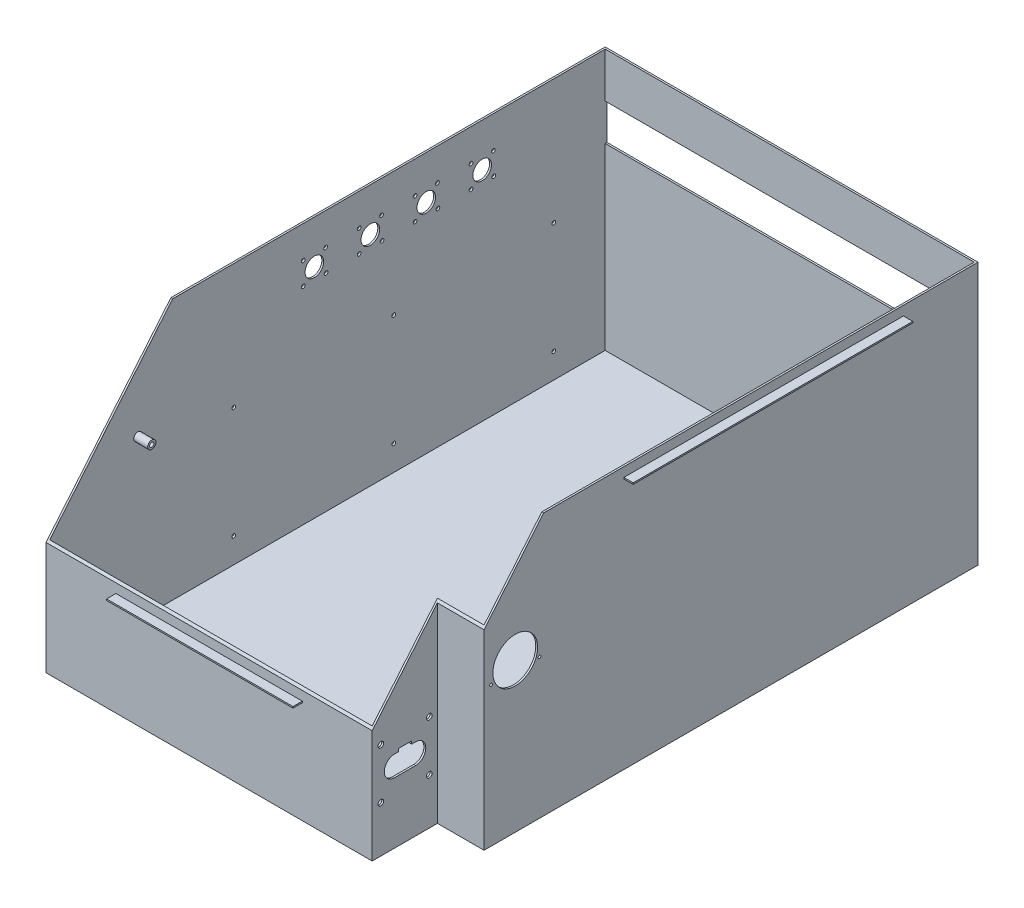
SolidWorks part; units mm, degrees
ref_plane "Front Plane" through (0, 0, 0) normal (0, 0, 1) x (1, 0, 0)
ref_plane "Top Plane" through (0, 0, 0) normal (0, 1, 0) x (1, 0, 0)
ref_plane "Right Plane" through (0, 0, 0) normal (1, 0, 0) x (0, 0, -1)
sketch "Sketch1" plane through (0, 0, 0) normal (0, 1, 0) x (1, 0, 0)
  line L1 (-200, 237.8263) -> (200, 237.8263)
  line L2 (-200, 237.8263) -> (-200, -362.1737)
  line L3 (-200, -362.1737) -> (150, -362.1737)
  line L4 (200, 237.8263) -> (200, -292.1737)
  line L6 (200, -292.1737) -> (150, -292.1737)
  line L7 (150, -292.1737) -> (150, -362.1737)
  line L8 (0, -55) -> (0, 55) construction
  point P1 (0, 237.8263)
  dimension "D1" = 600
  dimension "D2" = 400
  dimension "D5" = 70
  dimension "D6" = 50
extrude "Boss-Extrude1" add sketch "Sketch1" along normal blind 1.5
sketch "Sketch2" plane through (0, 1.5, 0) normal (0, 1, 0) x (1, 0, 0)
  line L60 (-198, 235.8263) -> (-198, -360.1737)
  line L61 (-198, -360.1737) -> (148, -360.1737)
  line L62 (148, -360.1737) -> (148, -290.1737)
  line L63 (148, -290.1737) -> (198, -290.1737)
  line L64 (198, -290.1737) -> (198, 235.8263)
  line L65 (198, 235.8263) -> (-198, 235.8263)
  line L66 (-200, 237.8263) -> (-200, -362.1737)
  line L67 (-200, -362.1737) -> (150, -362.1737)
  line L68 (150, -362.1737) -> (150, -292.1737)
  line L69 (150, -292.1737) -> (200, -292.1737)
  line L70 (200, -292.1737) -> (200, 237.8263)
  line L71 (200, 237.8263) -> (-200, 237.8263)
  line L72 (-200, 237.8263) -> (-200, -362.1737)
  line L73 (-200, -362.1737) -> (150, -362.1737)
  line L74 (150, -362.1737) -> (150, -292.1737)
  line L75 (150, -292.1737) -> (200, -292.1737)
  line L76 (200, -292.1737) -> (200, 237.8263)
  line L77 (200, 237.8263) -> (-200, 237.8263)
  dimension "D3" = 2
  dimension "D4" = 2
  dimension "D2" = 2
  dimension "D5" = 2
  dimension "D6" = 2
  dimension "D1" = 0
extrude "Boss-Extrude2" add sketch "Sketch2" along normal blind 280
sketch "Sketch3" plane through (-200, 0, 0) normal (-1, 0, 0) x (0, 0, 1)
  line L3 (362.1737, 281.5) -> (362.1737, 0) construction
  line L4 (362.1737, 121.1176) -> (228.1952, 281.5)
  line L6 (-237.8263, 281.5) -> (362.1737, 281.5) construction
  line L9 (362.1737, 281.5) -> (362.1737, 121.1176)
  line L10 (228.1952, 281.5) -> (362.1737, 281.5)
sketch "Sketch4" plane through (0, 0, -237.8263) normal (0, 0, -1) x (-1, 0, 0)
  line L0 (-200, 281.5) -> (-200, 0) construction
  line L1 (-200, 234.6761) -> (200, 234.6761)
  line L2 (-200, 234.6761) -> (-200, 192.2905)
  line L3 (-200, 192.2905) -> (200, 192.2905)
  line L4 (200, 234.6761) -> (200, 192.2905)
  line L5 (200, 281.5) -> (200, 0) construction
extrude "Boss-Extrude3" add sketch "Sketch4" against normal blind 2
extrude "Cut-Extrude1" cut sketch "Sketch3" against normal through all both and the other way through all
sketch "Sketch5" plane through (-200, 0, 0) normal (-1, 0, 0) x (0, 0, 1)
  line L0 (-115.8263, 223.1206) -> (-115.8263, 247.1206) construction
  line L5 (-115.8263, 223.1206) -> (-91.8263, 223.1206) construction
  line L6 (-115.8263, 247.1206) -> (-91.8263, 247.1206) construction
  line L7 (-91.8263, 223.1206) -> (-91.8263, 247.1206) construction
  line L8 (-115.8263, 223.1206) -> (-91.8263, 247.1206) construction
  line L9 (-115.8263, 247.1206) -> (-91.8263, 223.1206) construction
  line L10 (-55.8263, 223.1206) -> (-55.8263, 247.1206) construction
  line L11 (-55.8263, 223.1206) -> (-31.8263, 223.1206) construction
  line L12 (-55.8263, 247.1206) -> (-31.8263, 247.1206) construction
  line L13 (-31.8263, 223.1206) -> (-31.8263, 247.1206) construction
  line L14 (-55.8263, 223.1206) -> (-31.8263, 247.1206) construction
  line L15 (-55.8263, 247.1206) -> (-31.8263, 223.1206) construction
  line L16 (4.1737, 223.1206) -> (4.1737, 247.1206) construction
  line L17 (4.1737, 223.1206) -> (28.1737, 223.1206) construction
  line L18 (4.1737, 247.1206) -> (28.1737, 247.1206) construction
  line L19 (28.1737, 223.1206) -> (28.1737, 247.1206) construction
  line L20 (4.1737, 223.1206) -> (28.1737, 247.1206) construction
  line L21 (4.1737, 247.1206) -> (28.1737, 223.1206) construction
  line L22 (64.1737, 223.1206) -> (64.1737, 247.1206) construction
  line L23 (64.1737, 223.1206) -> (88.1737, 223.1206) construction
  line L24 (64.1737, 247.1206) -> (88.1737, 247.1206) construction
  line L25 (88.1737, 223.1206) -> (88.1737, 247.1206) construction
  line L26 (64.1737, 223.1206) -> (88.1737, 247.1206) construction
  line L27 (64.1737, 247.1206) -> (88.1737, 223.1206) construction
  line L28 (-235.8263, 281.5) -> (-235.8263, 1.5) construction
  circle A0 centre (-115.8263, 247.1206) radius 2
  circle A1 centre (-116.3263, 223.1259) radius 2
  circle A2 centre (-91.8263, 223.1206) radius 2
  circle A3 centre (-91.8263, 247.1206) radius 2
  circle A4 centre (-103.8263, 235.1206) radius 10
  circle A5 centre (-55.8263, 247.1206) radius 2
  circle A6 centre (-56.3263, 223.1259) radius 2
  circle A7 centre (-31.8263, 223.1206) radius 2
  circle A8 centre (-31.8263, 247.1206) radius 2
  circle A9 centre (-43.8263, 235.1206) radius 10
  circle A10 centre (4.1737, 247.1206) radius 2
  circle A11 centre (3.6737, 223.1259) radius 2
  circle A12 centre (28.1737, 223.1206) radius 2
  circle A13 centre (28.1737, 247.1206) radius 2
  circle A14 centre (16.1737, 235.1206) radius 10
  circle A15 centre (64.1737, 247.1206) radius 2
  circle A16 centre (63.6737, 223.1259) radius 2
  circle A17 centre (88.1737, 223.1206) radius 2
  circle A18 centre (88.1737, 247.1206) radius 2
  circle A19 centre (76.1737, 235.1206) radius 10
  point P9 (-103.8263, 235.1206)
  point P24 (-43.8263, 235.1206)
  point P38 (16.1737, 235.1206)
  point P52 (76.1737, 235.1206)
  dimension "D2" = 20
  dimension "D5" = 4
  dimension "D1" = 24
  dimension "D3" = 24
  dimension "D4" = 24
  dimension "D7" = 120
  dimension "D6" = 4
sketch "Sketch6" plane through (-198, 0, 0) normal (1, 0, 0) x (0, 0, -1)
  arc A0 (151.1392, 167.4539) -> (156.7272, 167.4539) centre (153.9332, 167.4539) ccw construction
  arc A1 (-68.8756, 167.4539) -> (-63.2876, 167.4539) centre (-66.0816, 167.4539) ccw construction
  arc A2 (-178.883, 167.4539) -> (-173.295, 167.4539) centre (-176.089, 167.4539) ccw construction
  arc A3 (151.1392, 167.4539) -> (156.7272, 167.4539) centre (153.9332, 167.4539) ccw
  arc A4 (-68.8756, 167.4539) -> (-63.2876, 167.4539) centre (-66.0816, 167.4539) ccw
  arc A5 (-178.883, 167.4539) -> (-173.295, 167.4539) centre (-176.089, 167.4539) ccw
  circle A6 centre (-176.089, 167.4539) radius 2.794
  circle A7 centre (-176.089, 167.4539) radius 4.5
  circle A8 centre (-64.4633, 167.4539) radius 4.5
  circle A9 centre (-64.4633, 167.4539) radius 2.794
  circle A10 centre (155.5515, 167.4539) radius 2.794
  circle A11 centre (155.5515, 167.4539) radius 4.5
  dimension "D1" = 9
extrude "Boss-Extrude4" [suppressed] add sketch "Sketch6" along normal blind 50 contours A4 A9 | A8 | A7 | A6 | A11 | A10
sketch "Sketch8" plane through (-198, 0, 0) normal (1, 0, 0) x (0, 0, -1)
  line L0 (235.8263, 1.5) -> (-360.1737, 1.5) construction
  line L1 (-360.1737, 123.5117) -> (-360.1737, 1.5) construction
  circle A0 centre (-265.6737, 172.1992) radius 2.39
  circle A1 centre (-265.6737, 172.1992) radius 4.39
  circle A2 centre (-265.1737, 16.5) radius 2.39
  circle A3 centre (-265.1737, 16.5) radius 4.39
  dimension "D3" = 4.78
  dimension "D4" = 2
  dimension "D1" = 155.7
  dimension "D2" = 15
  dimension "D5" = 95
extrude "Boss-Extrude5" add sketch "Sketch8" along normal blind 15
sketch "Sketch10" plane through (148, 0, 0) normal (-1, 0, 0) x (0, 0, 1)
  line L0 (315.6737, 86.5) -> (320.9237, 86.5) construction
  line L1 (315.6737, 66.5) -> (338.1737, 66.5) construction
  line L2 (338.1737, 76.5) -> (315.6737, 76.5) construction
  line L3 (360.1737, 1.5) -> (290.1737, 1.5) construction
  line L5 (320.9237, 86.5) -> (320.9237, 89.5) construction
  line L6 (320.9237, 89.5) -> (332.9237, 89.5) construction
  line L7 (332.9237, 86.5) -> (332.9237, 89.5) construction
  line L8 (360.1737, 123.5117) -> (360.1737, 1.5) construction
  line L9 (332.9237, 86.5) -> (338.1737, 86.5) construction
  line L10 (319.9237, 90.5) -> (333.9237, 90.5)
  line L11 (333.9237, 87.5) -> (333.9237, 90.5)
  line L12 (333.9237, 87.5) -> (338.1737, 87.5)
  line L13 (315.6737, 65.5) -> (338.1737, 65.5)
  line L14 (315.6737, 87.5) -> (319.9237, 87.5)
  line L15 (319.9237, 87.5) -> (319.9237, 90.5)
  line L17 (300.9737, 49.55) -> (352.8737, 49.55) construction
  line L18 (300.9737, 49.55) -> (300.9737, 103.45) construction
  line L19 (300.9737, 103.45) -> (352.8737, 103.45) construction
  line L20 (352.8737, 49.55) -> (352.8737, 103.45) construction
  line L21 (300.9737, 49.55) -> (352.8737, 103.45) construction
  line L22 (300.9737, 103.45) -> (352.8737, 49.55) construction
  arc A0 (315.6737, 86.5) -> (315.6737, 66.5) centre (315.6737, 76.5) ccw construction
  arc A1 (338.1737, 66.5) -> (338.1737, 86.5) centre (338.1737, 76.5) ccw construction
  arc A2 (338.1737, 65.5) -> (338.1737, 87.5) centre (338.1737, 76.5) ccw
  arc A3 (315.6737, 87.5) -> (315.6737, 65.5) centre (315.6737, 76.5) ccw
  circle A4 centre (300.9737, 103.45) radius 3
  circle A5 centre (352.8737, 103.45) radius 3
  circle A6 centre (300.9737, 49.55) radius 3
  circle A7 centre (352.8737, 49.55) radius 3
  point P12 (326.9237, 89.5)
  point P13 (326.9237, 76.5)
  point P26 (326.9237, 76.5)
  dimension "D1" = 65
  dimension "D2" = 22.5
  dimension "D6" = 20
  dimension "D10" = 6
  dimension "D3" = 22
  dimension "D4" = 12
  dimension "D5" = 3
  dimension "D8" = 51.9
  dimension "D9" = 53.9
  dimension "D7" = 1
extrude "Cut-Extrude2" cut sketch "Sketch10" against normal up to surface (2 mm away)
sketch "Sketch11" plane through (148, 0, 0) normal (-1, 0, 0) x (0, 0, 1)
  line L0 (298.4737, 103.43) -> (298.4737, 49.53) construction
  line L13 (315.6737, 66.5) -> (338.1737, 66.5) construction
  line L14 (315.6737, 86.5) -> (320.9237, 86.5) construction
  line L15 (315.6737, 66.5) -> (338.1737, 66.5)
  line L19 (315.6737, 86.5) -> (318.4237, 86.5)
  line L20 (333.9237, 90.5) -> (319.9237, 90.5)
  line L21 (333.9237, 90.5) -> (319.9237, 90.5)
  line L22 (333.9237, 87.5) -> (333.9237, 90.5)
  line L23 (333.9237, 87.5) -> (333.9237, 90.5)
  line L28 (330.4237, 86.5) -> (320.9237, 86.5)
  line L29 (315.7815, 66) -> (338.2021, 66)
  line L30 (330.9237, 86) -> (320.2852, 86)
  line L31 (330.9237, 86) -> (330.9237, 91)
  line L32 (330.9237, 91) -> (317.9237, 91)
  line L33 (317.9237, 91) -> (317.9237, 87)
  line L34 (315.7815, 87) -> (317.9237, 87)
  line L36 (298.4737, 103.43) -> (350.3737, 103.43) construction
  line L43 (333.9237, 90.5) -> (319.9237, 90.5)
  line L44 (333.9237, 90.5) -> (319.9237, 90.5)
  line L45 (333.9237, 87.5) -> (333.9237, 90.5)
  line L46 (333.9237, 87.5) -> (333.9237, 90.5)
  line L47 (338.1737, 87.5) -> (333.9237, 87.5)
  line L48 (338.1737, 87.5) -> (333.9237, 87.5)
  line L49 (315.6737, 65.5) -> (338.1737, 65.5)
  line L50 (315.6737, 65.5) -> (338.1737, 65.5)
  line L51 (319.9237, 87.5) -> (315.6737, 87.5)
  line L52 (319.9237, 87.5) -> (315.6737, 87.5)
  line L53 (319.9237, 90.5) -> (319.9237, 87.5)
  line L54 (319.9237, 90.5) -> (319.9237, 87.5)
  line L55 (333.9237, 90.5) -> (319.9237, 90.5)
  line L56 (333.9237, 90.5) -> (319.9237, 90.5)
  line L57 (333.9237, 87.5) -> (333.9237, 90.5)
  line L58 (333.9237, 87.5) -> (333.9237, 90.5)
  line L59 (338.1737, 87.5) -> (333.9237, 87.5)
  line L60 (338.1737, 87.5) -> (333.9237, 87.5)
  line L61 (315.6737, 65.5) -> (338.1737, 65.5)
  line L62 (315.6737, 65.5) -> (338.1737, 65.5)
  line L63 (319.9237, 87.5) -> (315.6737, 87.5)
  line L64 (319.9237, 87.5) -> (315.6737, 87.5)
  line L65 (319.9237, 90.5) -> (319.9237, 87.5)
  line L66 (319.9237, 90.5) -> (319.9237, 87.5)
  line L67 (330.4237, 86.5) -> (330.4237, 90.5) construction
  line L68 (330.4237, 90.5) -> (318.4237, 90.5) construction
  line L69 (318.4237, 90.5) -> (318.4237, 86.5) construction
  line L70 (338.1737, 87.5) -> (333.9237, 87.5)
  line L71 (338.1737, 87.5) -> (333.9237, 87.5)
  line L72 (315.6737, 65.5) -> (338.1737, 65.5)
  line L73 (315.6737, 65.5) -> (338.1737, 65.5)
  line L74 (319.9237, 87.5) -> (315.6737, 87.5)
  line L75 (319.9237, 87.5) -> (315.6737, 87.5)
  line L76 (319.9237, 90.5) -> (319.9237, 87.5)
  line L77 (319.9237, 90.5) -> (319.9237, 87.5)
  arc A4 (338.2021, 66) -> (320.2852, 86) centre (336.3485, 82.3648) ccw
  arc A5 (338.1737, 65.5) -> (338.1737, 87.5) centre (338.1737, 76.5) ccw
  arc A7 (338.1737, 65.5) -> (338.1737, 87.5) centre (338.1737, 76.5) ccw
  arc A9 (315.7815, 87) -> (315.7815, 66) centre (311.0911, 76.5) ccw
  circle A10 centre (298.4737, 103.43) radius 3
  circle A11 centre (298.4737, 49.53) radius 3
  circle A12 centre (350.3737, 103.43) radius 3
  circle A13 centre (350.3737, 49.53) radius 3
  arc A16 (338.1737, 66.5) -> (320.9237, 86.5) centre (336.3485, 82.3648) ccw construction
  arc A17 (338.1737, 65.5) -> (338.1737, 87.5) centre (338.1737, 76.5) ccw
  arc A18 (315.6737, 87.5) -> (315.6737, 65.5) centre (315.6737, 76.5) ccw
  arc A19 (315.6737, 87.5) -> (315.6737, 65.5) centre (315.6737, 76.5) ccw
  arc A20 (315.6737, 86.5) -> (315.6737, 66.5) centre (311.0911, 76.5) ccw construction
  arc A21 (338.1737, 65.5) -> (338.1737, 87.5) centre (338.1737, 76.5) ccw
  arc A22 (315.6737, 87.5) -> (315.6737, 65.5) centre (315.6737, 76.5) ccw
  arc A23 (315.6737, 87.5) -> (315.6737, 65.5) centre (315.6737, 76.5) ccw
  arc A24 (338.1737, 65.5) -> (338.1737, 87.5) centre (338.1737, 76.5) ccw
  arc A25 (338.1737, 65.5) -> (338.1737, 87.5) centre (338.1737, 76.5) ccw
  arc A26 (315.6737, 87.5) -> (315.6737, 65.5) centre (315.6737, 76.5) ccw
  arc A27 (315.6737, 87.5) -> (315.6737, 65.5) centre (315.6737, 76.5) ccw
  dimension "D5" = 6
  dimension "D6" = 51.9
  dimension "D7" = 53.9
  dimension "D1" = 0
  dimension "D2" = 0
  dimension "D3" = 0
  dimension "D4" = 0.5
extrude "Cut-Extrude3" [suppressed] cut sketch "Sketch11" against normal through all
sketch "Sketch14" plane through (148, 0, 0) normal (-1, 0, 0) x (0, 0, 1)
  line L0 (362.1737, 121.1176) -> (362.1737, 0) construction
  line L1 (362.1737, 0) -> (292.1737, 0) construction
  circle A0 centre (297.2737, 103.43) radius 3
  circle A1 centre (349.1737, 103.43) radius 3
  circle A2 centre (349.1737, 49.53) radius 3
  circle A3 centre (297.2737, 49.53) radius 3
  dimension "D5" = 6
  dimension "D1" = 51.9
  dimension "D2" = 53.9
  dimension "D3" = 13
  dimension "D4" = 103.43
extrude "Cut-Extrude4" [suppressed] cut sketch "Sketch14" against normal up to surface (1.5 mm away)
sketch "Sketch15" plane through (198, 0, 0) normal (-1, 0, 0) x (0, 0, 1)
  line L1 (-223.8263, 252.1363) -> (-208.8263, 252.1363)
  line L2 (-223.8263, 252.1363) -> (-223.8263, 250.6363)
  line L3 (-223.8263, 250.6363) -> (-208.8263, 250.6363)
  line L4 (-208.8263, 252.1363) -> (-208.8263, 250.6363)
  line L5 (-235.8263, 281.5) -> (-235.8263, 1.5) construction
  line L6 (196.1737, 252.1363) -> (211.1737, 252.1363)
  line L7 (196.1737, 250.6363) -> (211.1737, 250.6363)
  line L8 (196.1737, 252.1363) -> (196.1737, 250.6363)
  line L9 (211.1737, 252.1363) -> (211.1737, 250.6363)
  dimension "D1" = 1.5
  dimension "D2" = 15
  dimension "D3" = 12
  dimension "D4" = 432
  dimension "D5" = 15
extrude "Boss-Extrude6" add sketch "Sketch15" along normal blind 15
ref_plane "Plane1" through (0, 0, -203.8263) normal (0, 0, -1) x (-1, 0, 0)
sketch "Sketch17" plane through (0, 0, -208.8263) normal (0, 0, 1) x (1, 0, 0)
  line L0 (198, 250.6363) -> (198, 235.6363)
  line L1 (198, 281.5) -> (198, 207.307) construction
  line L2 (198, 235.6363) -> (183, 250.6363)
  line L3 (183, 250.6363) -> (198, 250.6363)
  dimension "D1" = 15
extrude "Boss-Extrude7" add sketch "Sketch17" against normal blind 1.5
ref_plane "Plane2" through (0, 0, 191.1737) normal (0, 0, 1) x (1, 0, 0)
sketch "Sketch18" plane through (0, 0, 196.1737) normal (0, 0, 1) x (1, 0, 0)
  line L0 (198, 250.6363) -> (198, 235.6363)
  line L1 (198, 281.5) -> (198, 207.307) construction
  line L2 (198, 235.6363) -> (183, 250.6363)
  line L3 (183, 250.6363) -> (198, 250.6363)
  dimension "D1" = 15
extrude "Boss-Extrude8" add sketch "Sketch18" along normal blind 1.5
sketch "Sketch20" plane through (0, 252.1363, 0) normal (0, 1, 0) x (1, 0, 0)
  line L1 (183, 223.8263) -> (198, 223.8263) construction
  line L2 (183, 208.8263) -> (183, 223.8263) construction
  line L3 (183, -211.1737) -> (198, -211.1737) construction
  line L4 (183, -211.1737) -> (183, -196.1737) construction
  circle A0 centre (190.5, 216.3263) radius 2.4159
  circle A1 centre (190.5, -203.6737) radius 2
  dimension "D3" = 4
  dimension "D1" = 7.5
  dimension "D2" = 7.5
  dimension "D4" = 7.5
  dimension "D5" = 7.5
extrude "Cut-Extrude5" cut sketch "Sketch20" against normal up to surface (1.5 mm away) up to face at (190.5, 250.6363, -217.0763)
extrude "Cut-Extrude7" cut sketch "Sketch5" against normal up to surface (2 mm away) up to face at (-198, 16.5, 260.7837)
sketch "Sketch21" plane through (0, 0, -237.8263) normal (0, 0, -1) x (-1, 0, 0)
  line L0 (-200, 281.5) -> (200, 281.5) construction
  line L1 (-150, 271.5) -> (150, 271.5)
  line L2 (-150, 271.5) -> (-150, 270)
  line L3 (-150, 270) -> (150, 270)
  line L4 (150, 271.5) -> (150, 270)
  point P6 (0, 281.5)
  point P7 (0, 271.5)
  dimension "D1" = 1.5
  dimension "D2" = 300
  dimension "D3" = 10
extrude "Boss-Extrude9" add sketch "Sketch21" along normal blind 10
sketch "Sketch22" plane through (-200, 0, 0) normal (-1, 0, 0) x (0, 0, 1)
  line L0 (-237.8263, 281.5) -> (228.1952, 281.5) construction
  line L1 (-157.8263, 271.5) -> (142.1737, 271.5)
  line L2 (-157.8263, 271.5) -> (-157.8263, 270)
  line L3 (-157.8263, 270) -> (142.1737, 270)
  line L4 (142.1737, 271.5) -> (142.1737, 270)
  line L5 (-237.8263, 281.5) -> (-237.8263, 0) construction
  dimension "D1" = 1.5
  dimension "D2" = 10
  dimension "D3" = 80
  dimension "D4" = 300
extrude "Boss-Extrude10" add sketch "Sketch22" along normal blind 10
ref_plane "Plane3" through (0, 0, -77.8263) normal (0, 0, -1) x (-1, 0, 0)
sketch "Sketch23" plane through (0, 0, -77.8263) normal (0, 0, -1) x (-1, 0, 0)
  line L0 (210, 270) -> (200, 270) construction
  line L1 (210, 270) -> (200, 270)
  line L2 (210, 270) -> (200, 260)
  line L3 (200, 281.5) -> (200, 0) construction
  line L4 (200, 260) -> (200, 270)
  dimension "D1" = 10
extrude "Boss-Extrude11" add sketch "Sketch23" along normal mid plane 1.5
ref_plane "Plane4" through (0, 0, 52.1737) normal (0, 0, 1) x (1, 0, 0)
sketch "Sketch24" plane through (0, 0, 52.1737) normal (0, 0, 1) x (1, 0, 0)
  line L6 (-210, 270) -> (-200, 260)
  line L7 (-200, 260) -> (-200, 270)
  line L8 (-200, 270) -> (-210, 270)
  line L9 (-210, 270) -> (-200, 260)
  line L10 (-200, 260) -> (-200, 270)
  line L11 (-200, 270) -> (-210, 270)
  dimension "D1" = 0
extrude "Boss-Extrude12" add sketch "Sketch24" along normal mid plane 1.5
ref_plane "Plane5" through (100, 0, 0) normal (1, 0, 0) x (0, 0, -1)
sketch "Sketch25" plane through (100, 0, 0) normal (1, 0, 0) x (0, 0, -1)
  line L0 (247.8263, 270) -> (237.8263, 270)
  line L1 (237.8263, 270) -> (237.8263, 260)
  line L2 (237.8263, 281.5) -> (237.8263, 0) construction
  line L3 (237.8263, 260) -> (247.8263, 270)
  dimension "D1" = 10
extrude "Boss-Extrude13" add sketch "Sketch25" along normal mid plane 1.5
ref_plane "Plane6" through (-100, 0, 0) normal (-1, 0, 0) x (0, 0, 1)
sketch "Sketch26" plane through (-100, 0, 0) normal (-1, 0, 0) x (0, 0, 1)
  line L3 (-247.8263, 270) -> (-237.8263, 260)
  line L4 (-237.8263, 260) -> (-237.8263, 270)
  line L5 (-237.8263, 270) -> (-247.8263, 270)
  line L6 (-247.8263, 270) -> (-237.8263, 260)
  line L7 (-237.8263, 260) -> (-237.8263, 270)
  line L8 (-237.8263, 270) -> (-247.8263, 270)
  dimension "D1" = 0
extrude "Boss-Extrude14" add sketch "Sketch26" along normal mid plane 1.5
mirror "Mirror1" about plane through (0, 0, 0) normal (1, 0, 0) of "Boss-Extrude11", "Boss-Extrude12", "Boss-Extrude10"
sketch "Sketch27" plane through (0, 0, 362.1737) normal (0, 0, 1) x (1, 0, 0)
  line L0 (150, 121.1176) -> (-200, 121.1176) construction
  line L1 (-125, 111.1176) -> (75, 111.1176)
  line L2 (-125, 111.1176) -> (-125, 109.6176)
  line L3 (-125, 109.6176) -> (75, 109.6176)
  line L4 (75, 111.1176) -> (75, 109.6176)
  line L5 (150, 121.1176) -> (-200, 121.1176) construction
  point P6 (-25, 121.1176)
  point P7 (-25, 111.1176)
  dimension "D1" = 1.5
  dimension "D2" = 200
  dimension "D3" = 10
extrude "Boss-Extrude15" add sketch "Sketch27" along normal blind 10
ref_plane "Plane7" through (-95, 0, 0) normal (-1, 0, 0) x (0, 0, 1)
sketch "Sketch28" plane through (-95, 0, 0) normal (-1, 0, 0) x (0, 0, 1)
  line L0 (372.1737, 109.6176) -> (362.1737, 109.6176)
  line L1 (362.1737, 109.6176) -> (362.1737, 99.6176)
  line L2 (362.1737, 121.1176) -> (362.1737, 0) construction
  line L3 (362.1737, 99.6176) -> (372.1737, 109.6176)
  dimension "D1" = 10
extrude "Boss-Extrude16" add sketch "Sketch28" along normal mid plane 1.5
ref_plane "Plane8" through (45, 0, 0) normal (1, 0, 0) x (0, 0, -1)
sketch "Sketch29" plane through (45, 0, 0) normal (1, 0, 0) x (0, 0, -1)
  line L3 (-372.1737, 109.6176) -> (-362.1737, 99.6176)
  line L4 (-362.1737, 99.6176) -> (-362.1737, 109.6176)
  line L5 (-362.1737, 109.6176) -> (-372.1737, 109.6176)
  line L6 (-372.1737, 109.6176) -> (-362.1737, 99.6176)
  line L7 (-362.1737, 99.6176) -> (-362.1737, 109.6176)
  line L8 (-362.1737, 109.6176) -> (-372.1737, 109.6176)
  dimension "D1" = 0
extrude "Boss-Extrude17" add sketch "Sketch29" along normal mid plane 1.5
sketch "Sketch30" plane through (200, 0, 0) normal (1, 0, 0) x (0, 0, -1)
  line L1 (-292.1737, 0) -> (237.8263, 0) construction
  line L2 (-292.1737, 204.9129) -> (-292.1737, 0) construction
  circle A0 centre (-258.6737, 160) radius 24
  circle A1 centre (-284.6737, 150) radius 1.5
  circle A2 centre (-232.6737, 150) radius 1.5
  dimension "D1" = 48
  dimension "D2" = 3
  dimension "D3" = 3
  dimension "D4" = 26
  dimension "D5" = 10
  dimension "D6" = 26
  dimension "D7" = 10
  dimension "D8" = 160
  dimension "D9" = 33.5
extrude "Cut-Extrude8" cut sketch "Sketch30" against normal up to surface (2 mm away) up to face at (198, 246.1363, -214.3263)
sketch "Sketch33" plane through (-200, 0, 0) normal (-1, 0, 0) x (0, 0, 1)
  line L0 (-237.8263, 281.5) -> (-237.8263, 0) construction
  line L1 (-237.8263, 0) -> (362.1737, 0) construction
  circle A0 centre (-180.6263, 147.77) radius 2
  circle A1 centre (-180.6263, 28.39) radius 2
  circle A2 centre (-8.9263, 147.77) radius 2
  circle A3 centre (-8.9263, 28.39) radius 2
  circle A4 centre (162.7737, 147.77) radius 2
  circle A5 centre (162.7737, 28.39) radius 2
  dimension "D3" = 4
  dimension "D1" = 57.2
  dimension "D2" = 119.38
  dimension "D4" = 28.39
  dimension "D5" = 3
extrude "Cut-Extrude9" cut sketch "Sketch33" against normal up to surface (2 mm away) up to face at (-198, 223.1206, 26.1737)
sketch "Sketch42" plane through (0, 0, -235.8263) normal (0, 0, 1) x (1, 0, 0)
  line L0 (-198, 233.18) -> (198, 233.18)
  line L1 (-198, 281.5) -> (-198, 1.5) construction
  line L2 (198, 281.5) -> (198, 1.5) construction
  line L3 (198, 281.5) -> (-198, 281.5) construction
  line L4 (198, 193.79) -> (-198, 193.79)
  line L5 (198, 193.79) -> (198, 233.18)
  line L6 (-198, 193.79) -> (-198, 233.18)
  dimension "D1" = 48.32
extrude "Cut-Extrude13" cut sketch "Sketch42" against normal blind 40 contours L6 L0 L5 L4
